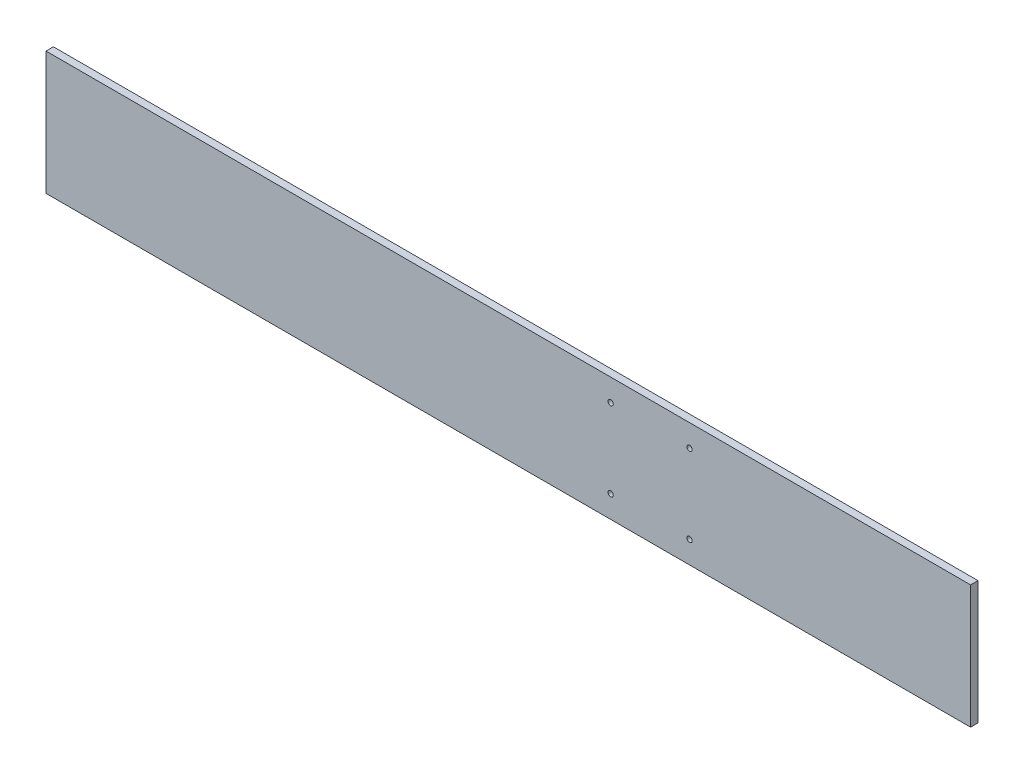
SolidWorks part; units mm, degrees
ref_plane "Plan de face" through (0, 0, 0) normal (0, 0, 1) x (1, 0, 0)
ref_plane "Plan de dessus" through (0, 0, 0) normal (0, 1, 0) x (1, 0, 0)
ref_plane "Plan de droite" through (0, 0, 0) normal (1, 0, 0) x (0, 0, -1)
sketch "Esquisse1" plane through (0, 0, 0) normal (0, 0, 1) x (1, 0, 0)
  line L1 (-375, -50) -> (375, -50)
  line L2 (-375, -50) -> (-375, 50)
  line L3 (-375, 50) -> (375, 50)
  line L4 (375, -50) -> (375, 50)
  line L5 (-375, -50) -> (375, 50) construction
  line L6 (-375, 50) -> (375, -50) construction
  point P0 (0, 0)
  dimension "D1" = 100
  dimension "D2" = 750
extrude "Boss.-Extru.1" add sketch "Esquisse1" along normal blind 6
hole_wizard "Dégagement M43" positions "Esquisse6" profile "Esquisse7" hole size "M4" standard "ISO" end condition through all
sketch "Esquisse6" plane through (111.0283, 8.0627, -3) normal (0, 0, -1) x (-1, 0, 0)
  point P0 (28.0283, -40.0627)
sketch "Esquisse7" plane through (83, -32, -3) normal (1, 0, 0) x (0, 1, 0)
  line L0 (0, 0) -> (0, 9)
  line L1 (0, 9) -> (2.15, 9)
  line L2 (2.15, 9) -> (2.15, 0)
  line L3 (2.15, 0) -> (0, 0)
  line L4 (0, -6.35) -> (0, 107.95) construction
  dimension "Diamètre du perçage jusqu'au prochain" = 4.3
  dimension "Profondeur du perçage jusqu'au prochain" = 9
pattern_linear "Répétition linéaire1" count 2 spacing 64 along (1, 0, 0) count 2 spacing 64 along (0, 1, 0) of "Dégagement M43"
